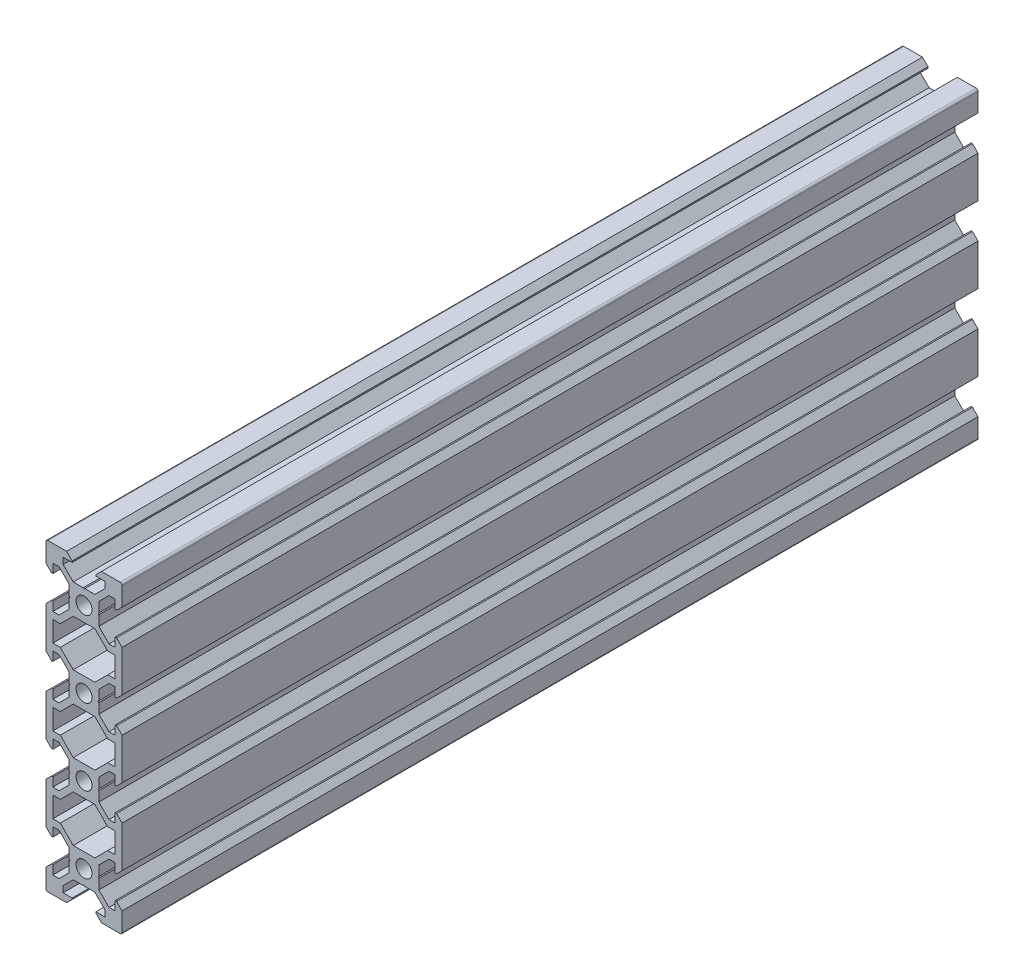
SolidWorks part; units mm, degrees
material "6061-T6 (SS)"
ref_plane "Front Plane" through (0, 0, 0) normal (0, 0, 1) x (1, 0, 0)
ref_plane "Top Plane" through (0, 0, 0) normal (0, 1, 0) x (1, 0, 0)
ref_plane "Right Plane" through (0, 0, 0) normal (1, 0, 0) x (0, 0, -1)
sketch "Sketch1" plane through (0, 0, 0) normal (0, 0, 1) x (1, 0, 0)
  line L0 (0, 0) -> (10, 0) construction
  line L1 (9.5, -40) -> (-9.5, -40)
  line L2 (10, -39.5) -> (10, 39.5)
  line L3 (9.5, 40) -> (-9.5, 40)
  line L4 (-10, -39.5) -> (-10, 39.5)
  line L5 (10, -40) -> (-10, 40) construction
  line L6 (10, 40) -> (-10, -40) construction
  circle A0 centre (0, 30) radius 2.1
  circle A1 centre (0, 10) radius 2.1
  circle A2 centre (0, -10) radius 2.1
  circle A3 centre (0, -30) radius 2.1
  arc A4 (-9.5, -40) -> (-10, -39.5) centre (-9.5, -39.5) cw
  arc A5 (9.5, -40) -> (10, -39.5) centre (9.5, -39.5) ccw
  arc A6 (10, 39.5) -> (9.5, 40) centre (9.5, 39.5) ccw
  arc A7 (-9.5, 40) -> (-10, 39.5) centre (-9.5, 39.5) ccw
  point P0 (0, 0)
  line B0 (0, 30) -> (0, 40) construction
  line B1 (0, 33.69) -> (-0.21, 33.9)
  line B2 (-0.21, 33.9) -> (-2.8393, 33.9)
  line B3 (-2.8393, 33.9) -> (-5.5, 36.5607)
  line B4 (-5.5, 36.5607) -> (-5.5, 38.2)
  line B5 (-5.5, 38.2) -> (-3.125, 38.2)
  line B6 (-3.125, 38.2) -> (-3.125, 38.545)
  line B7 (-3.125, 38.545) -> (-4.58, 40)
  line B8 (-4.58, 40) -> (4.58, 40)
  line B9 (0, 30) -> (-5.9132, 35.9132) construction
  line B10 (3.125, 38.545) -> (4.58, 40)
  line B11 (3.125, 38.2) -> (3.125, 38.545)
  line B12 (5.5, 38.2) -> (3.125, 38.2)
  line B13 (5.5, 36.5607) -> (5.5, 38.2)
  line B14 (2.8393, 33.9) -> (5.5, 36.5607)
  line B15 (0.21, 33.9) -> (2.8393, 33.9)
  line B16 (0, 33.69) -> (0.21, 33.9)
  line B17 (0, 30) -> (-10, 30) construction
  line B18 (-3.69, 30) -> (-3.9, 29.79)
  line B19 (-3.9, 29.79) -> (-3.9, 27.1607)
  line B20 (-3.9, 27.1607) -> (-6.5607, 24.5)
  line B21 (-6.5607, 24.5) -> (-8.2, 24.5)
  line B22 (-8.2, 24.5) -> (-8.2, 26.875)
  line B23 (-8.2, 26.875) -> (-8.545, 26.875)
  line B24 (-8.545, 26.875) -> (-10, 25.42)
  line B25 (-10, 25.42) -> (-10, 34.58)
  line B26 (0, 30) -> (-5.9132, 24.0868) construction
  line B27 (-8.545, 33.125) -> (-10, 34.58)
  line B28 (-8.2, 33.125) -> (-8.545, 33.125)
  line B29 (-8.2, 35.5) -> (-8.2, 33.125)
  line B30 (-6.5607, 35.5) -> (-8.2, 35.5)
  line B31 (-3.9, 32.8393) -> (-6.5607, 35.5)
  line B32 (-3.9, 30.21) -> (-3.9, 32.8393)
  line B33 (-3.69, 30) -> (-3.9, 30.21)
  line B34 (0, 10) -> (-10, 10) construction
  line B35 (-3.69, 10) -> (-3.9, 9.79)
  line B36 (-3.9, 9.79) -> (-3.9, 7.1607)
  line B37 (-3.9, 7.1607) -> (-6.5607, 4.5)
  line B38 (-6.5607, 4.5) -> (-8.2, 4.5)
  line B39 (-8.2, 4.5) -> (-8.2, 6.875)
  line B40 (-8.2, 6.875) -> (-8.545, 6.875)
  line B41 (-8.545, 6.875) -> (-10, 5.42)
  line B42 (-10, 5.42) -> (-10, 14.58)
  line B43 (0, 10) -> (-5.9132, 4.0868) construction
  line B44 (-8.545, 13.125) -> (-10, 14.58)
  line B45 (-8.2, 13.125) -> (-8.545, 13.125)
  line B46 (-8.2, 15.5) -> (-8.2, 13.125)
  line B47 (-6.5607, 15.5) -> (-8.2, 15.5)
  line B48 (-3.9, 12.8393) -> (-6.5607, 15.5)
  line B49 (-3.9, 10.21) -> (-3.9, 12.8393)
  line B50 (-3.69, 10) -> (-3.9, 10.21)
  line B51 (0, -10) -> (-10, -10) construction
  line B52 (-3.69, -10) -> (-3.9, -10.21)
  line B53 (-3.9, -10.21) -> (-3.9, -12.8393)
  line B54 (-3.9, -12.8393) -> (-6.5607, -15.5)
  line B55 (-6.5607, -15.5) -> (-8.2, -15.5)
  line B56 (-8.2, -15.5) -> (-8.2, -13.125)
  line B57 (-8.2, -13.125) -> (-8.545, -13.125)
  line B58 (-8.545, -13.125) -> (-10, -14.58)
  line B59 (-10, -14.58) -> (-10, -5.42)
  line B60 (0, -10) -> (-5.9132, -15.9132) construction
  line B61 (-8.545, -6.875) -> (-10, -5.42)
  line B62 (-8.2, -6.875) -> (-8.545, -6.875)
  line B63 (-8.2, -4.5) -> (-8.2, -6.875)
  line B64 (-6.5607, -4.5) -> (-8.2, -4.5)
  line B65 (-3.9, -7.1607) -> (-6.5607, -4.5)
  line B66 (-3.9, -9.79) -> (-3.9, -7.1607)
  line B67 (-3.69, -10) -> (-3.9, -9.79)
  line B68 (0, -30) -> (-10, -30) construction
  line B69 (-3.69, -30) -> (-3.9, -30.21)
  line B70 (-3.9, -30.21) -> (-3.9, -32.8393)
  line B71 (-3.9, -32.8393) -> (-6.5607, -35.5)
  line B72 (-6.5607, -35.5) -> (-8.2, -35.5)
  line B73 (-8.2, -35.5) -> (-8.2, -33.125)
  line B74 (-8.2, -33.125) -> (-8.545, -33.125)
  line B75 (-8.545, -33.125) -> (-10, -34.58)
  line B76 (-10, -34.58) -> (-10, -25.42)
  line B77 (0, -30) -> (-5.9132, -35.9132) construction
  line B78 (-8.545, -26.875) -> (-10, -25.42)
  line B79 (-8.2, -26.875) -> (-8.545, -26.875)
  line B80 (-8.2, -24.5) -> (-8.2, -26.875)
  line B81 (-6.5607, -24.5) -> (-8.2, -24.5)
  line B82 (-3.9, -27.1607) -> (-6.5607, -24.5)
  line B83 (-3.9, -29.79) -> (-3.9, -27.1607)
  line B84 (-3.69, -30) -> (-3.9, -29.79)
  line B85 (0, -30) -> (0, -40) construction
  line B86 (0, -33.69) -> (0.21, -33.9)
  line B87 (0.21, -33.9) -> (2.8393, -33.9)
  line B88 (2.8393, -33.9) -> (5.5, -36.5607)
  line B89 (5.5, -36.5607) -> (5.5, -38.2)
  line B90 (5.5, -38.2) -> (3.125, -38.2)
  line B91 (3.125, -38.2) -> (3.125, -38.545)
  line B92 (3.125, -38.545) -> (4.58, -40)
  line B93 (4.58, -40) -> (-4.58, -40)
  line B94 (0, -30) -> (5.9132, -35.9132) construction
  line B95 (-3.125, -38.545) -> (-4.58, -40)
  line B96 (-3.125, -38.2) -> (-3.125, -38.545)
  line B97 (-5.5, -38.2) -> (-3.125, -38.2)
  line B98 (-5.5, -36.5607) -> (-5.5, -38.2)
  line B99 (-2.8393, -33.9) -> (-5.5, -36.5607)
  line B100 (-0.21, -33.9) -> (-2.8393, -33.9)
  line B101 (0, -33.69) -> (-0.21, -33.9)
  line B102 (0, -30) -> (10, -30) construction
  line B103 (3.69, -30) -> (3.9, -29.79)
  line B104 (3.9, -29.79) -> (3.9, -27.1607)
  line B105 (3.9, -27.1607) -> (6.5607, -24.5)
  line B106 (6.5607, -24.5) -> (8.2, -24.5)
  line B107 (8.2, -24.5) -> (8.2, -26.875)
  line B108 (8.2, -26.875) -> (8.545, -26.875)
  line B109 (8.545, -26.875) -> (10, -25.42)
  line B110 (10, -25.42) -> (10, -34.58)
  line B111 (0, -30) -> (5.9132, -24.0868) construction
  line B112 (8.545, -33.125) -> (10, -34.58)
  line B113 (8.2, -33.125) -> (8.545, -33.125)
  line B114 (8.2, -35.5) -> (8.2, -33.125)
  line B115 (6.5607, -35.5) -> (8.2, -35.5)
  line B116 (3.9, -32.8393) -> (6.5607, -35.5)
  line B117 (3.9, -30.21) -> (3.9, -32.8393)
  line B118 (3.69, -30) -> (3.9, -30.21)
  line B119 (0, -10) -> (10, -10) construction
  line B120 (3.69, -10) -> (3.9, -9.79)
  line B121 (3.9, -9.79) -> (3.9, -7.1607)
  line B122 (3.9, -7.1607) -> (6.5607, -4.5)
  line B123 (6.5607, -4.5) -> (8.2, -4.5)
  line B124 (8.2, -4.5) -> (8.2, -6.875)
  line B125 (8.2, -6.875) -> (8.545, -6.875)
  line B126 (8.545, -6.875) -> (10, -5.42)
  line B127 (10, -5.42) -> (10, -14.58)
  line B128 (0, -10) -> (5.9132, -4.0868) construction
  line B129 (8.545, -13.125) -> (10, -14.58)
  line B130 (8.2, -13.125) -> (8.545, -13.125)
  line B131 (8.2, -15.5) -> (8.2, -13.125)
  line B132 (6.5607, -15.5) -> (8.2, -15.5)
  line B133 (3.9, -12.8393) -> (6.5607, -15.5)
  line B134 (3.9, -10.21) -> (3.9, -12.8393)
  line B135 (3.69, -10) -> (3.9, -10.21)
  line B136 (0, 10) -> (10, 10) construction
  line B137 (3.69, 10) -> (3.9, 10.21)
  line B138 (3.9, 10.21) -> (3.9, 12.8393)
  line B139 (3.9, 12.8393) -> (6.5607, 15.5)
  line B140 (6.5607, 15.5) -> (8.2, 15.5)
  line B141 (8.2, 15.5) -> (8.2, 13.125)
  line B142 (8.2, 13.125) -> (8.545, 13.125)
  line B143 (8.545, 13.125) -> (10, 14.58)
  line B144 (10, 14.58) -> (10, 5.42)
  line B145 (0, 10) -> (5.9132, 15.9132) construction
  line B146 (8.545, 6.875) -> (10, 5.42)
  line B147 (8.2, 6.875) -> (8.545, 6.875)
  line B148 (8.2, 4.5) -> (8.2, 6.875)
  line B149 (6.5607, 4.5) -> (8.2, 4.5)
  line B150 (3.9, 7.1607) -> (6.5607, 4.5)
  line B151 (3.9, 9.79) -> (3.9, 7.1607)
  line B152 (3.69, 10) -> (3.9, 9.79)
  line B153 (0, 30) -> (10, 30) construction
  line B154 (3.69, 30) -> (3.9, 30.21)
  line B155 (3.9, 30.21) -> (3.9, 32.8393)
  line B156 (3.9, 32.8393) -> (6.5607, 35.5)
  line B157 (6.5607, 35.5) -> (8.2, 35.5)
  line B158 (8.2, 35.5) -> (8.2, 33.125)
  line B159 (8.2, 33.125) -> (8.545, 33.125)
  line B160 (8.545, 33.125) -> (10, 34.58)
  line B161 (10, 34.58) -> (10, 25.42)
  line B162 (0, 30) -> (5.9132, 35.9132) construction
  line B163 (8.545, 26.875) -> (10, 25.42)
  line B164 (8.2, 26.875) -> (8.545, 26.875)
  line B165 (8.2, 24.5) -> (8.2, 26.875)
  line B166 (6.5607, 24.5) -> (8.2, 24.5)
  line B167 (3.9, 27.1607) -> (6.5607, 24.5)
  line B168 (3.9, 29.79) -> (3.9, 27.1607)
  line B169 (3.69, 30) -> (3.9, 29.79)
  line B170 (-8.2, 17.3) -> (-8.2, 22.7)
  line B171 (-8.2, 22.7) -> (-6.2393, 22.7)
  line B172 (-6.2393, 22.7) -> (-2.8393, 26.1)
  line B173 (-2.8393, 26.1) -> (2.8393, 26.1)
  line B174 (0, 26.1) -> (0, 20) construction
  line B175 (0, 20) -> (-8.2, 20) construction
  line B176 (6.2393, 22.7) -> (2.8393, 26.1)
  line B177 (8.2, 22.7) -> (6.2393, 22.7)
  line B178 (8.2, 17.3) -> (8.2, 22.7)
  line B179 (8.2, 17.3) -> (6.2393, 17.3)
  line B180 (6.2393, 17.3) -> (2.8393, 13.9)
  line B181 (-2.8393, 13.9) -> (2.8393, 13.9)
  line B182 (-6.2393, 17.3) -> (-2.8393, 13.9)
  line B183 (-8.2, 17.3) -> (-6.2393, 17.3)
  line B184 (0, 26.1) -> (0, 30) construction
  line B185 (0, 30) -> (-5.0927, 24.9073) construction
  line B186 (-8.2, -2.7) -> (-8.2, 2.7)
  line B187 (-8.2, 2.7) -> (-6.2393, 2.7)
  line B188 (-6.2393, 2.7) -> (-2.8393, 6.1)
  line B189 (-2.8393, 6.1) -> (2.8393, 6.1)
  line B190 (0, 6.1) -> (0, 0) construction
  line B191 (0, 0) -> (-8.2, 0) construction
  line B192 (6.2393, 2.7) -> (2.8393, 6.1)
  line B193 (8.2, 2.7) -> (6.2393, 2.7)
  line B194 (8.2, -2.7) -> (8.2, 2.7)
  line B195 (8.2, -2.7) -> (6.2393, -2.7)
  line B196 (6.2393, -2.7) -> (2.8393, -6.1)
  line B197 (-2.8393, -6.1) -> (2.8393, -6.1)
  line B198 (-6.2393, -2.7) -> (-2.8393, -6.1)
  line B199 (-8.2, -2.7) -> (-6.2393, -2.7)
  line B200 (0, 6.1) -> (0, 10) construction
  line B201 (0, 10) -> (-5.0927, 4.9073) construction
  line B202 (-8.2, -22.7) -> (-8.2, -17.3)
  line B203 (-8.2, -17.3) -> (-6.2393, -17.3)
  line B204 (-6.2393, -17.3) -> (-2.8393, -13.9)
  line B205 (-2.8393, -13.9) -> (2.8393, -13.9)
  line B206 (0, -13.9) -> (0, -20) construction
  line B207 (0, -20) -> (-8.2, -20) construction
  line B208 (6.2393, -17.3) -> (2.8393, -13.9)
  line B209 (8.2, -17.3) -> (6.2393, -17.3)
  line B210 (8.2, -22.7) -> (8.2, -17.3)
  line B211 (8.2, -22.7) -> (6.2393, -22.7)
  line B212 (6.2393, -22.7) -> (2.8393, -26.1)
  line B213 (-2.8393, -26.1) -> (2.8393, -26.1)
  line B214 (-6.2393, -22.7) -> (-2.8393, -26.1)
  line B215 (-8.2, -22.7) -> (-6.2393, -22.7)
  line B216 (0, -13.9) -> (0, -10) construction
  line B217 (0, -10) -> (-5.0927, -15.0927) construction
  dimension "D5" = 4.2
  dimension "D6" = 0.5
  dimension "D1" = 20
  dimension "D2" = 80
  dimension "D3" = 20
  dimension "D4" = 20
sketch_block_instance "V Slot 1-4"
sketch_block "V Slot 1" parameters "D1"=10, "D2"=11, "D3"=4.3, "D4"=1.8, "D5"=0.21, "D6"=45, "D7"=9.16, "D8"=1.5, "D9"=6.25
sketch_block_instance "V Slot 1-5"
sketch_block_instance "V Slot 1-6"
sketch_block_instance "V Slot 1-7"
sketch_block_instance "V Slot 1-8"
sketch_block_instance "V Slot 1-9"
sketch_block_instance "V Slot 1-10"
sketch_block_instance "V Slot 1-11"
sketch_block_instance "V Slot 1-12"
sketch_block_instance "V Slot 1-13"
sketch_block_instance "Center Cutout 1-1"
sketch_block "Center Cutout 1" parameters "D1"=5.4, "D2"=12.2, "D3"=8.2, "D4"=45, "D5"=10, "D6"=1.5
sketch_block_instance "Center Cutout 1-2"
sketch_block_instance "Center Cutout 1-3"
extrude "Boss-Extrude1" add sketch "Sketch1" along normal blind 225 contours B169 B154 B155 B156 B157 B158 B159 B160 L2 A6 L3 B10 B11 B12 B13 B14 B15 B16 B1 B2 B3 B4 B5 B6 B7 A7 L4 B27 B28 B29 B30 B31 B32 B33 B18 B19 B20 B21 B22 B23 B24 B44 B45 B46 B47 B48 B49 B50 B35
